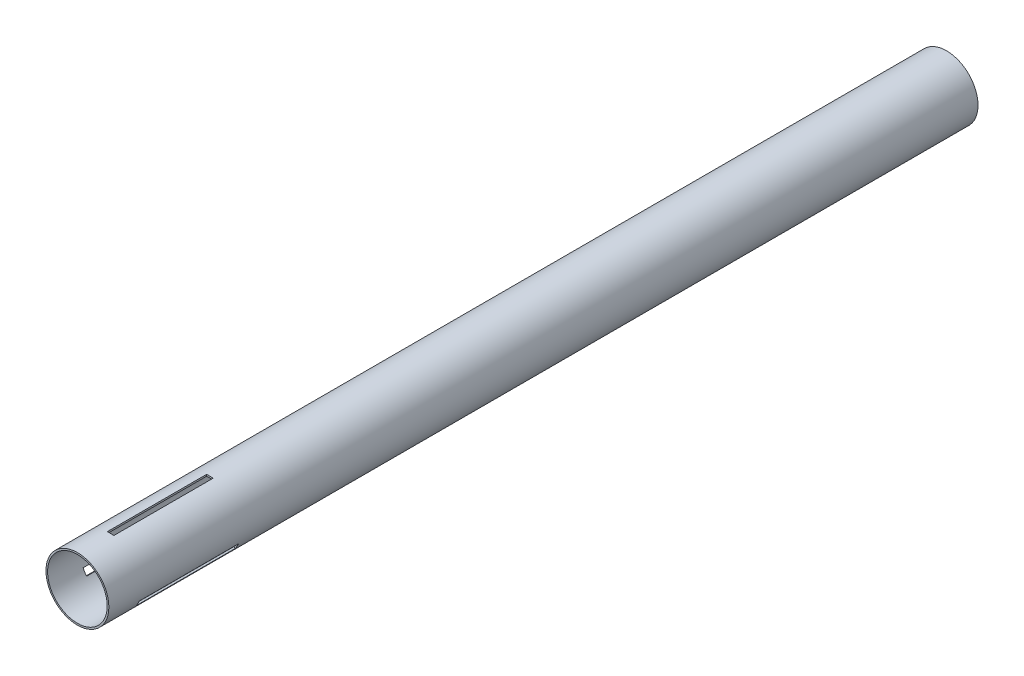
SolidWorks part; units mm, degrees
ref_plane "Front Plane" through (0, 0, 0) normal (0, 0, 1) x (1, 0, 0)
ref_plane "Top Plane" through (0, 0, 0) normal (0, 1, 0) x (1, 0, 0)
ref_plane "Right Plane" through (0, 0, 0) normal (1, 0, 0) x (0, 0, -1)
sketch "Sketch1" plane through (0, 0, 0) normal (0, 0, 1) x (1, 0, 0)
  circle A0 centre (0, 0) radius 19
  circle A1 centre (0, 0) radius 18
  dimension "D1" = 38
  dimension "D2" = 1
extrude "Boss-Extrude1" add sketch "Sketch1" along normal blind 525
ref_plane "Plane1" through (0, 19, 0) normal (0, 1, 0) x (1, 0, 0)
sketch "Sketch2" plane through (0, 19, 0) normal (0, 1, 0) x (1, 0, 0)
  line L2 (2, -505) -> (2, -445)
  line L3 (-2, -505) -> (-2, -445)
  line L4 (-2, -445) -> (2, -445)
  line L5 (-2, -505) -> (2, -505)
  dimension "D1" = 60
extrude "Cut-Extrude1" cut sketch "Sketch2" against normal up to next
pattern_circular "CirPattern1" count 3 every 120 about axis through (0, 0, 0) along (0, 0, 1) of "Cut-Extrude1"
